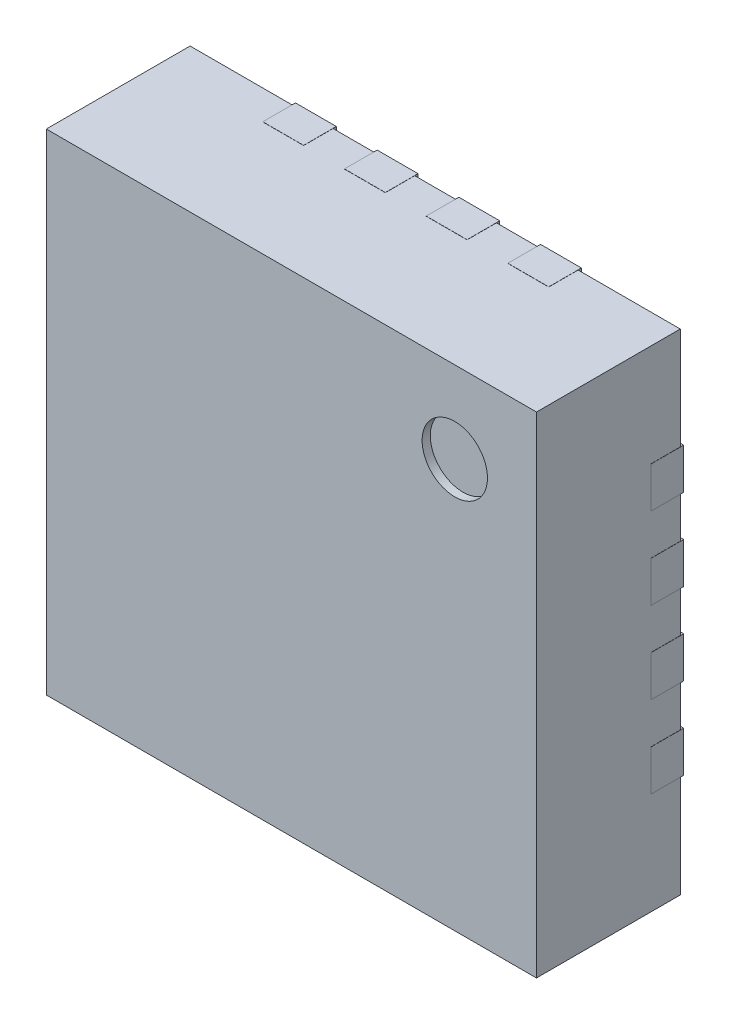
SolidWorks part; units mm, degrees
ref_plane "Front Plane" through (0, 0, 0) normal (0, 0, 1) x (1, 0, 0)
ref_plane "Top Plane" through (0, 0, 0) normal (0, 1, 0) x (1, 0, 0)
ref_plane "Right Plane" through (0, 0, 0) normal (1, 0, 0) x (0, 0, -1)
ref_plane "Plane1" through (0, 0, 0.02) normal (0, 0, 1) x (1, 0, 0)
sketch "Sketch1" plane through (0, 0, 0.02) normal (0, 0, 1) x (1, 0, 0)
  line L1 (-1.5, 1.5) -> (1.5, 1.5)
  line L2 (-1.5, 1.5) -> (-1.5, -1.5)
  line L3 (-1.5, -1.5) -> (1.5, -1.5)
  line L4 (1.5, 1.5) -> (1.5, -1.5)
extrude "Extrude1" add sketch "Sketch1" along normal blind 0.88
sketch "Sketch2" plane through (0, 0, 0) normal (0, 0, 1) x (1, 0, 0)
  line L1 (0.6, 0.9) -> (0.9, 0.6)
  line L2 (0.825, 1.1) -> (0.875, 1.15)
  line L3 (-0.875, 1.15) -> (-0.825, 1.1)
  line L4 (-0.375, 1.501) -> (-0.125, 1.501)
  line L5 (-0.875, 1.501) -> (-0.625, 1.501)
  line L6 (-0.875, 1.501) -> (-0.875, 1.15)
  line L7 (-0.825, 1.1) -> (-0.625, 1.1)
  line L8 (-0.625, 1.501) -> (-0.625, 1.1)
  line L9 (-0.375, 1.501) -> (-0.375, 1.1)
  line L10 (-0.375, 1.1) -> (-0.125, 1.1)
  line L11 (-0.125, 1.501) -> (-0.125, 1.1)
  line L12 (0.125, 1.501) -> (0.375, 1.501)
  line L13 (0.125, 1.501) -> (0.125, 1.1)
  line L14 (0.125, 1.1) -> (0.375, 1.1)
  line L15 (0.375, 1.501) -> (0.375, 1.1)
  line L16 (0.625, 1.501) -> (0.875, 1.501)
  line L17 (-1.501, 0.625) -> (-1.501, 0.875)
  line L18 (0.875, -1.501) -> (0.875, -1.15)
  line L19 (0.625, -1.1) -> (0.825, -1.1)
  line L20 (0.625, -1.501) -> (0.625, -1.1)
  line L21 (0.625, -1.501) -> (0.875, -1.501)
  line L22 (0.375, -1.501) -> (0.375, -1.1)
  line L23 (0.125, -1.1) -> (0.375, -1.1)
  line L24 (0.125, -1.501) -> (0.125, -1.1)
  line L25 (0.125, -1.501) -> (0.375, -1.501)
  line L26 (-0.125, -1.501) -> (-0.125, -1.1)
  line L27 (-0.375, -1.1) -> (-0.125, -1.1)
  line L28 (-0.375, -1.501) -> (-0.375, -1.1)
  line L29 (-0.625, -1.501) -> (-0.625, -1.1)
  line L30 (-0.825, -1.1) -> (-0.625, -1.1)
  line L31 (-0.875, -1.501) -> (-0.875, -1.15)
  line L32 (-0.875, -1.501) -> (-0.625, -1.501)
  line L33 (-0.375, -1.501) -> (-0.125, -1.501)
  line L34 (-1.1, 0.625) -> (-1.1, 0.825)
  line L35 (1.501, -0.625) -> (1.1, -0.625)
  line L36 (1.501, 0.625) -> (1.1, 0.625)
  line L37 (1.501, -0.375) -> (1.501, -0.125)
  line L38 (-1.501, 0.875) -> (-1.15, 0.875)
  line L39 (1.501, -0.875) -> (1.15, -0.875)
  line L40 (-1.501, -0.375) -> (-1.1, -0.375)
  line L41 (1.501, 0.875) -> (1.15, 0.875)
  line L42 (1.501, 0.625) -> (1.501, 0.875)
  line L43 (1.1, -0.375) -> (1.1, -0.125)
  line L44 (-1.501, -0.625) -> (-1.1, -0.625)
  line L45 (-1.501, 0.125) -> (-1.501, 0.375)
  line L46 (1.501, 0.375) -> (1.1, 0.375)
  line L47 (1.501, -0.875) -> (1.501, -0.625)
  line L48 (-1.501, -0.375) -> (-1.501, -0.125)
  line L49 (1.501, -0.375) -> (1.1, -0.375)
  line L50 (-1.501, -0.875) -> (-1.15, -0.875)
  line L51 (-1.501, 0.125) -> (-1.1, 0.125)
  line L52 (-1.501, 0.375) -> (-1.1, 0.375)
  line L53 (-1.1, -0.375) -> (-1.1, -0.125)
  line L54 (-1.1, 0.125) -> (-1.1, 0.375)
  line L55 (-1.501, 0.625) -> (-1.1, 0.625)
  line L56 (1.501, 0.125) -> (1.1, 0.125)
  line L57 (1.501, 0.125) -> (1.501, 0.375)
  line L58 (1.501, -0.125) -> (1.1, -0.125)
  line L59 (-1.501, -0.875) -> (-1.501, -0.625)
  line L60 (1.1, 0.625) -> (1.1, 0.825)
  line L61 (-1.1, -0.825) -> (-1.1, -0.625)
  line L62 (-1.501, -0.125) -> (-1.1, -0.125)
  line L63 (1.1, 0.125) -> (1.1, 0.375)
  line L64 (1.1, -0.825) -> (1.1, -0.625)
  line L65 (-0.9, 0.9) -> (0.6, 0.9)
  line L66 (-0.9, 0.9) -> (-0.9, -0.9)
  line L67 (-0.9, -0.9) -> (0.9, -0.9)
  line L68 (0.9, 0.6) -> (0.9, -0.9)
  line L69 (-1.1, 0.825) -> (-1.15, 0.875)
  line L70 (0.625, 1.501) -> (0.625, 1.1)
  line L71 (-1.15, -0.875) -> (-1.1, -0.825)
  line L72 (-0.875, -1.15) -> (-0.825, -1.1)
  line L73 (0.825, -1.1) -> (0.875, -1.15)
  line L74 (1.15, -0.875) -> (1.1, -0.825)
  line L75 (1.1, 0.825) -> (1.15, 0.875)
  line L76 (0.625, 1.1) -> (0.825, 1.1)
  line L77 (0.875, 1.501) -> (0.875, 1.15)
  point P20 (0.875, -1.1)
  point P33 (-0.875, -1.1)
  point P38 (-1.1, -0.875)
  point P49 (-1.1, 0.875)
  point P53 (1.1, 0.875)
  point P66 (1.1, -0.875)
  point P68 (0.9, 0.9)
  point P86 (-0.875, 1.1)
  point P87 (0.875, 1.1)
extrude "Extrude2" add sketch "Sketch2" along normal blind 0.2
sketch "Sketch3" plane through (0, 0, 0.9) normal (0, 0, 1) x (1, 0, 0)
  circle A0 centre (1, 1) radius 0.2
extrude "Extrude3" cut sketch "Sketch3" against normal blind 0.05
